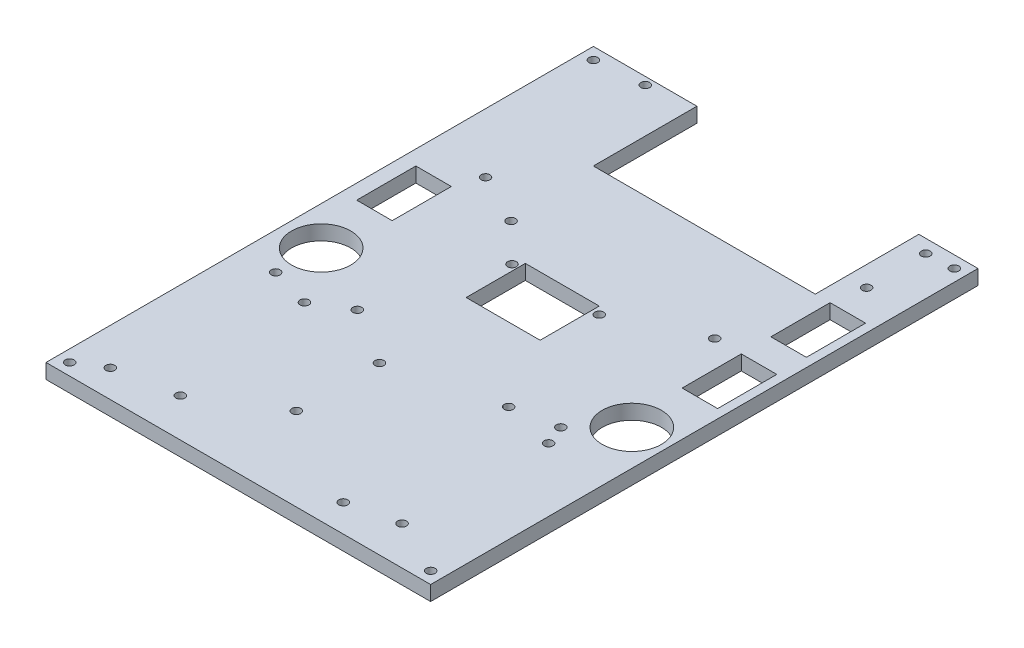
SolidWorks part; units mm, degrees
ref_plane "Front Plane" through (0, 0, 0) normal (0, 0, 1) x (1, 0, 0)
ref_plane "Top Plane" through (0, 0, 0) normal (0, 1, 0) x (1, 0, 0)
ref_plane "Right Plane" through (0, 0, 0) normal (1, 0, 0) x (0, 0, -1)
sketch "Sketch1" plane through (0, 0, 0) normal (0, 1, 0) x (1, 0, 0)
  line L0 (65, 192.587) -> (65, -112.4037) construction
  line L1 (0, 0) -> (130, 0)
  line L2 (0, 0) -> (0, 185)
  line L3 (0, 185) -> (35, 185)
  line L4 (130, 0) -> (130, 185)
  line L5 (-189.3262, 92.5) -> (226.1388, 92.5) construction
  line L6 (110, 185) -> (130, 185)
  line L7 (52, 110) -> (77, 110)
  line L8 (52, 110) -> (52, 90)
  line L9 (52, 90) -> (77, 90)
  line L10 (77, 110) -> (77, 90)
  line L12 (35, 185) -> (35, 150)
  line L13 (35, 150) -> (110, 150)
  line L14 (110, 185) -> (110, 150)
  line L16 (5, 120) -> (17, 120)
  line L17 (5, 120) -> (5, 100)
  line L18 (5, 100) -> (17, 100)
  line L19 (17, 120) -> (17, 100)
  line L20 (5, 120) -> (17, 100) construction
  line L21 (5, 100) -> (17, 120) construction
  line L22 (115, 120) -> (127, 120)
  line L23 (115, 120) -> (115, 100)
  line L24 (115, 100) -> (127, 100)
  line L25 (127, 120) -> (127, 100)
  line L26 (115, 120) -> (127, 100) construction
  line L27 (115, 100) -> (127, 120) construction
  line L28 (115, 150) -> (127, 150)
  line L29 (115, 150) -> (115, 130)
  line L30 (115, 130) -> (127, 130)
  line L31 (127, 150) -> (127, 130)
  line L32 (115, 150) -> (127, 130) construction
  line L33 (115, 130) -> (127, 150) construction
  circle A0 centre (126, 4) radius 1.5
  circle A1 centre (4, 4) radius 1.5
  circle A2 centre (4, 181) radius 1.5
  circle A3 centre (126, 181) radius 1.5
  circle A4 centre (13, 80) radius 10
  circle A5 centre (118, 80) radius 10
  circle A6 centre (79.5, 107.5) radius 1.5
  circle A7 centre (50, 107.5) radius 1.5
  circle A8 centre (20.0811, 128.4698) radius 1.4946
  circle A9 centre (116.7971, 180.5366) radius 1.5
  circle A10 centre (20.0811, 182.4698) radius 1.5
  circle A11 centre (116.7971, 160.5366) radius 1.5
  point P33 (11, 110)
  point P38 (121, 110)
  point P43 (121, 140)
  dimension "D3" = 4
  dimension "D4" = 4
  dimension "D5" = 3
  dimension "D6" = 4
  dimension "D8" = 20
  dimension "D9" = 20
  dimension "D10" = 80
  dimension "D11" = 80
  dimension "D12" = 12
  dimension "D13" = 13
  dimension "D18" = 3
  dimension "D19" = 3
  dimension "D20" = 2.5
  dimension "D21" = 2
  dimension "D22" = 2.5
  dimension "D23" = 2.5
  dimension "D39" = 2.9893
  dimension "D40" = 20.0811
  dimension "D41" = 56.5302
  dimension "D42" = 3
  dimension "D43" = 20.0811
  dimension "D44" = 2.5302
  dimension "D45" = 20
  dimension "D46" = 9.2029
  dimension "D47" = 4.4634
  dimension "D48" = 6.7971
  dimension "D1" = 130
  dimension "D2" = 185
  dimension "D7" = 4
  dimension "D14" = 25
  dimension "D15" = 20
  dimension "D16" = 90
  dimension "D17" = 52
  dimension "D24" = 75
  dimension "D25" = 35
  dimension "D26" = 35
  dimension "D27" = 20
  dimension "D28" = 12
  dimension "D29" = 5
  dimension "D30" = 20
  dimension "D31" = 10
  dimension "D32" = 20
  dimension "D33" = 12
  dimension "D34" = 12
  dimension "D35" = 3
  dimension "D36" = 3
  dimension "D37" = 20
  dimension "D38" = 20
extrude "Boss-Extrude2" add sketch "Sketch1" along normal blind 5
sketch "Sketch2" plane through (0, 5, 0) normal (0, 1, 0) x (1, 0, 0)
  line L0 (0, 185) -> (0, 0) construction
  line L5 (130, 0) -> (130, 185) construction
  line L6 (0, 0) -> (130, 0) construction
  circle A4 centre (12.4444, 65.1717) radius 1.5
  circle A5 centre (91.1844, 65.1717) radius 1.5
  circle A6 centre (91.1844, 9.2917) radius 1.5
  circle A7 centre (12.4444, 9.2917) radius 1.5
  dimension "D5" = 3
  dimension "D6" = 55.88
  dimension "D7" = 12.4444
  dimension "D8" = 38.8156
  dimension "D2" = 78.74
  dimension "D3" = 3
  dimension "D4" = 78.74
  dimension "D9" = 3
  dimension "D10" = 38.8156
  dimension "D11" = 3
  dimension "D12" = 55.88
  dimension "D13" = 9.2917
extrude "Cut-Extrude1" cut sketch "Sketch2" against normal blind 100
sketch "Sketch3" plane through (0, 5, 0) normal (0, 1, 0) x (1, 0, 0)
  line L0 (107.33, 13) -> (107.33, 76.7649) construction
  line L1 (32.4, 13) -> (32.4, 78.2621) construction
  line L3 (130, 0) -> (130, 185) construction
  line L4 (0, 185) -> (0, 0) construction
  line L5 (108.6, 61.26) -> (26.1, 61.26) construction
  line L6 (32.4, 13) -> (0, 13) construction
  line L7 (0, 0) -> (130, 0) construction
  circle A7 centre (108.6, 61.26) radius 1.5
  circle A8 centre (107.33, 13) radius 1.5
  circle A9 centre (32.4, 13) radius 1.5
  circle A10 centre (26.1, 61.26) radius 1.5
  circle A11 centre (56.53, 56.18) radius 1.5
  circle A12 centre (56.5, 28.1) radius 1.5
  dimension "D1" = 3
  dimension "D2" = 74.93
  dimension "D3" = 21.4
  dimension "D4" = 32.4
  dimension "D5" = 22.67
  dimension "D6" = 48.26
  dimension "D7" = 82.5
  dimension "D8" = 26.1
  dimension "D9" = 13
  dimension "D10" = 24.13
  dimension "D11" = 5.08
  dimension "D12" = 56.5
  dimension "D13" = 28.1
  dimension "D14" = 3
extrude "Cut-Extrude2" cut sketch "Sketch3" against normal blind 1220
sketch "Sketch5" plane through (0, 5, 0) normal (0, 1, 0) x (1, 0, 0)
  line L6 (130, 0) -> (130, 185) construction
  line L8 (110, 150) -> (35, 150) construction
  circle A0 centre (37.2, 120) radius 1.5
  circle A1 centre (106, 120) radius 1.5
  circle A2 centre (106, 68) radius 1.5
  circle A3 centre (37.2, 68) radius 1.5
  dimension "D6" = 24
  dimension "D7" = 3
  dimension "D3" = 30
  dimension "D2" = 24
  dimension "D4" = 3
  dimension "D8" = 68.8
  dimension "D9" = 52
  dimension "D11" = 3
  dimension "D12" = 3
  dimension "D13" = 68.8
extrude "Cut-Extrude4" cut sketch "Sketch5" against normal blind 10 contours A1 | A0 | A3 | A2
